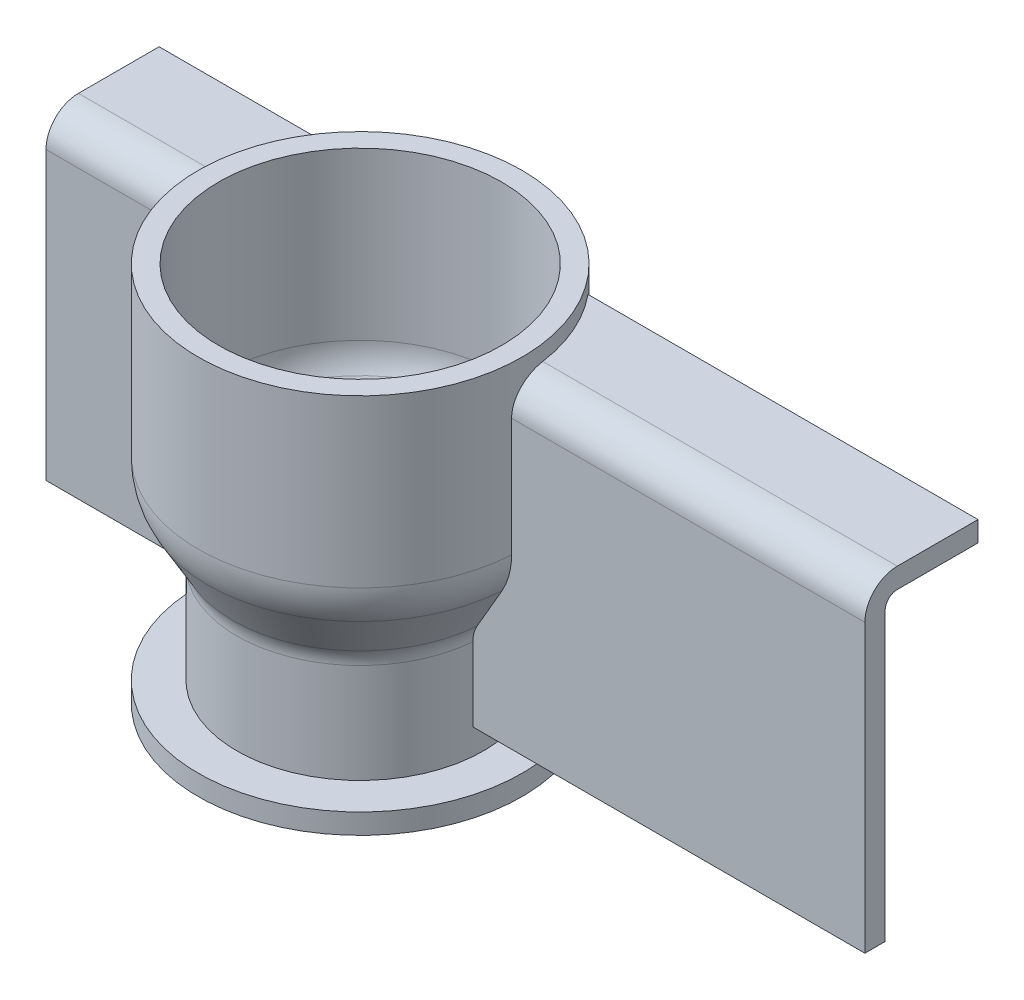
SolidWorks part; units mm, degrees
ref_plane "Front Plane" through (0, 0, 0) normal (0, 0, 1) x (1, 0, 0)
ref_plane "Top Plane" through (0, 0, 0) normal (0, 1, 0) x (1, 0, 0)
ref_plane "Right Plane" through (0, 0, 0) normal (1, 0, 0) x (0, 0, -1)
sketch "strainer" plane through (0, 0, 0) normal (0, 0, 1) x (1, 0, 0)
  line L0 (0, 0) -> (0, 47.8971) construction
  line L2 (-34.925, 0) -> (-34.925, -41.047)
  line L3 (-33.2235, -47.397) -> (-27.1015, -58.0007)
  line L4 (-25.4, -64.3507) -> (-25.4, -88.9)
  arc A0 (-25.4, -64.3507) -> (-27.1015, -58.0007) centre (-38.1, -64.3507) ccw
  arc A1 (-33.2235, -47.397) -> (-34.925, -41.047) centre (-22.225, -41.047) cw
  point P9 (-25.4, -60.9478)
  dimension "D6" = 12.7
  dimension "D1" = 69.85
  dimension "D2" = 27.9522
  dimension "D3" = 88.9
  dimension "D4" = 50.8
  dimension "D5" = 30
ref_plane "bracket.start" through (127, 0, 0) normal (1, 0, 0) x (0, 0, -1)
sketch "bracket" plane through (127, 0, 0) normal (1, 0, 0) x (0, 0, -1)
  line L0 (0, -6.35) -> (0, -82.55)
  line L1 (0, -6.35) -> (25.4, -6.35)
  dimension "D1" = 6.35
  dimension "D2" = 25.4
  dimension "D3" = 76.2
revolve "Revolve-Thin1" add sketch "strainer" angle 360 about L0
extrude "Extrude-Thin1" add sketch "bracket" against normal up to next thin contours L1 L0 thin type mid plane wall 5
sketch "Sketch2" plane through (0, -88.9, 0) normal (0, -1, 0) x (1, 0, 0)
  circle A0 centre (0, 0) radius 39.925 construction
  circle A1 centre (0, 0) radius 39.925
extrude "Boss-Extrude1" add sketch "Sketch2" along normal blind 5
ref_plane "Plane1" through (-75, 0, 0) normal (1, 0, 0) x (0, 0, -1)
sketch "Sketch4" plane through (-75, 0, 0) normal (1, 0, 0) x (0, 0, -1)
  line L6 (5.5, -8.85) -> (25.4, -8.85)
  line L7 (25.4, -8.85) -> (25.4, -3.85)
  line L8 (25.4, -3.85) -> (5.5, -3.85)
  line L9 (-2.5, -11.85) -> (-2.5, -82.55)
  line L10 (-2.5, -82.55) -> (2.5, -82.55)
  line L11 (2.5, -82.55) -> (2.5, -11.85)
  line L12 (5.5, -8.85) -> (25.4, -8.85)
  line L13 (25.4, -8.85) -> (25.4, -3.85)
  line L14 (25.4, -3.85) -> (5.5, -3.85)
  line L15 (-2.5, -11.85) -> (-2.5, -82.55)
  line L16 (-2.5, -82.55) -> (2.5, -82.55)
  line L17 (2.5, -82.55) -> (2.5, -11.85)
  arc A2 (5.5, -3.85) -> (-2.5, -11.85) centre (5.5, -11.85) ccw
  arc A3 (5.5, -8.85) -> (2.5, -11.85) centre (5.5, -11.85) ccw
  arc A4 (5.5, -3.85) -> (-2.5, -11.85) centre (5.5, -11.85) ccw
  arc A5 (5.5, -8.85) -> (2.5, -11.85) centre (5.5, -11.85) ccw
  dimension "D1" = 0
extrude "Boss-Extrude2" add sketch "Sketch4" along normal up to next
